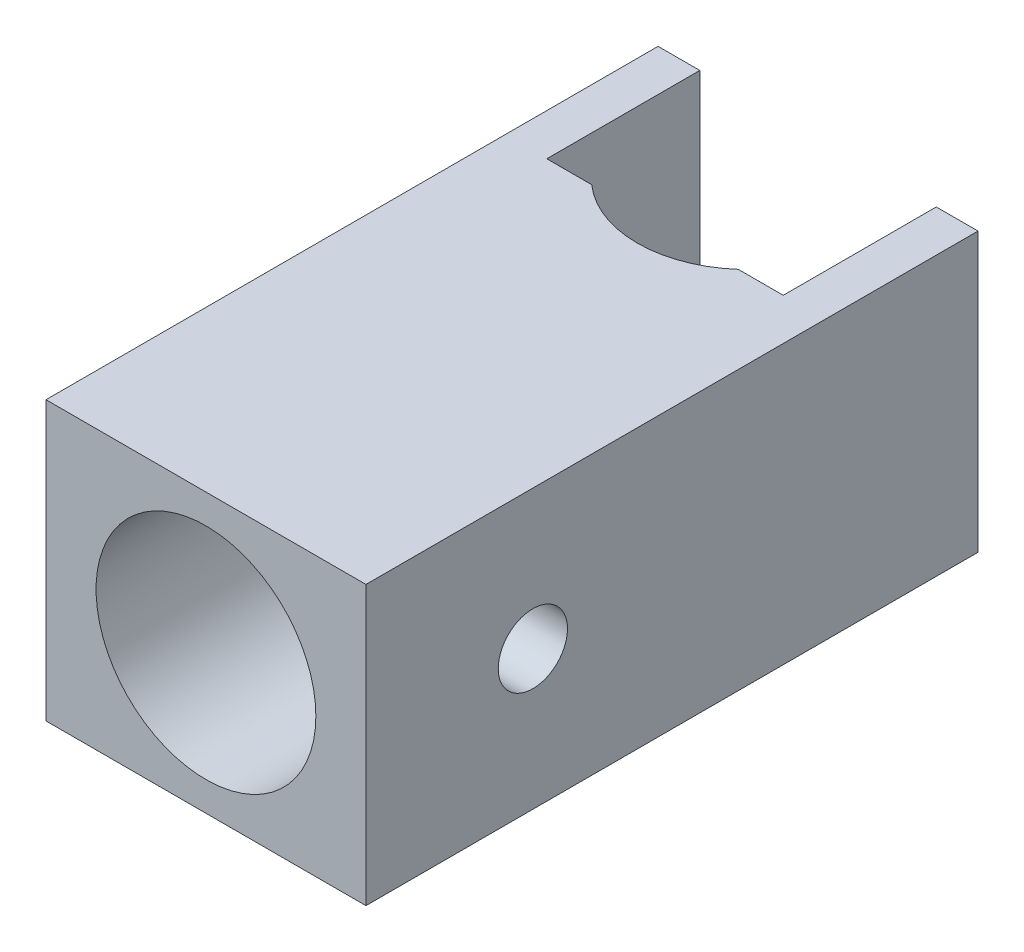
SolidWorks part; units mm, degrees
ref_plane "Front Plane" through (0, 0, 0) normal (0, 0, 1) x (1, 0, 0)
ref_plane "Top Plane" through (0, 0, 0) normal (0, 1, 0) x (1, 0, 0)
ref_plane "Right Plane" through (0, 0, 0) normal (1, 0, 0) x (0, 0, -1)
sketch "Sketch1" plane through (0, 0, 0) normal (0, 0, 1) x (1, 0, 0)
  line L1 (5.75, -5) -> (-5.75, -5)
  line L2 (5.75, -5) -> (5.75, 5)
  line L3 (5.75, 5) -> (-5.75, 5)
  line L4 (-5.75, -5) -> (-5.75, 5)
  line L5 (5.75, -5) -> (-5.75, 5) construction
  line L6 (5.75, 5) -> (-5.75, -5) construction
  circle A0 centre (0, 0) radius 3.95
  dimension "D1" = 7.9
  dimension "D2" = 11.5
  dimension "D3" = 10
extrude "Boss-Extrude1" add sketch "Sketch1" along normal blind 10
sketch "Sketch2" plane through (0, 0, 0) normal (0, 0, -1) x (-1, 0, 0)
  line L1 (5.75, -5) -> (-5.75, -5)
  line L2 (5.75, -5) -> (5.75, 5)
  line L3 (5.75, 5) -> (-5.75, 5)
  line L4 (-5.75, -5) -> (-5.75, 5)
  line L5 (5.75, -5) -> (-5.75, 5) construction
  line L6 (5.75, 5) -> (-5.75, -5) construction
  point P0 (0, 0)
extrude "Boss-Extrude2" add sketch "Sketch2" along normal blind 12
ref_plane "Plane1" through (0, 0, 0) normal (-1, 0, 0) x (0, 0, 1)
sketch "Sketch3" plane through (0, 0, 0) normal (-1, 0, 0) x (0, 0, 1)
  line L0 (-2.5, -5) -> (-3.5, -5)
  line L1 (-6.5, 5) -> (-12, 5)
  line L2 (-6.5, 5) -> (-6.5, 4.5)
  line L3 (10, 5) -> (-12, 5) construction
  line L4 (10, -5) -> (-12, -5) construction
  line L5 (-12, 5) -> (-12, -5)
  line L6 (-2.5, -5) -> (-2.5, 5)
  line L7 (-2.5, 5) -> (-6.5, 5)
  line L8 (-12, -5) -> (-3.5, -5)
  line L9 (-3.5, 1.7072) -> (-3.5, -5)
  line L10 (-12, -5) -> (-12, 5) construction
  arc A3 (-6.5, 4.5) -> (-3.5, 1.7072) centre (-6.3, 1.7072) cw
  point P7 (-2.7, -5)
  point P15 (0, 0)
  point P18 (-3.3797, -5)
  point P19 (-3.8776, -5)
  point P20 (-4.4948, 1.5)
  point P21 (-3.5, 2.3505)
  point P22 (-6, 2.3505)
  point P23 (-6.304, 2.0029)
  dimension "D3" = 2.5
  dimension "D2" = 2.8
  dimension "D1" = 0.5
  dimension "D4" = 4
  dimension "D6" = 1
extrude "Cut-Extrude1" cut sketch "Sketch3" against normal blind 4.25 and the other way blind 4.25
sketch "Sketch4" plane through (-5.75, 0, 0) normal (-1, 0, 0) x (0, 0, 1)
  line L0 (10, 5) -> (10, -5) construction
  line L1 (0, 0) -> (4, 0) construction
  circle A0 centre (4, 0) radius 1.245
  dimension "D2" = 2.49
  dimension "D1" = 6
extrude "Cut-Extrude2" cut sketch "Sketch4" against normal through all
sketch "Sketch5" plane through (0, 5, 0) normal (0, 1, 0) x (1, 0, 0)
  line L1 (-4.25, 6.5) -> (4.25, 6.5) construction
  line L2 (0, 0) -> (0, 9.4688) construction
  line L3 (-2.6339, 6.5) -> (2.6339, 6.5)
  circle A0 centre (0, 9.4688) radius 3.9688
  point P9 (-3.6983, 6.5)
  line M3 (4.25, 6.5) -> (-4.25, 6.5)
  dimension "D1" = 7.9375
  dimension "D2" = 1
extrude "Cut-Extrude3" cut sketch "Sketch5" against normal through all contours A0 L2 L3 | L2 A0 M3
